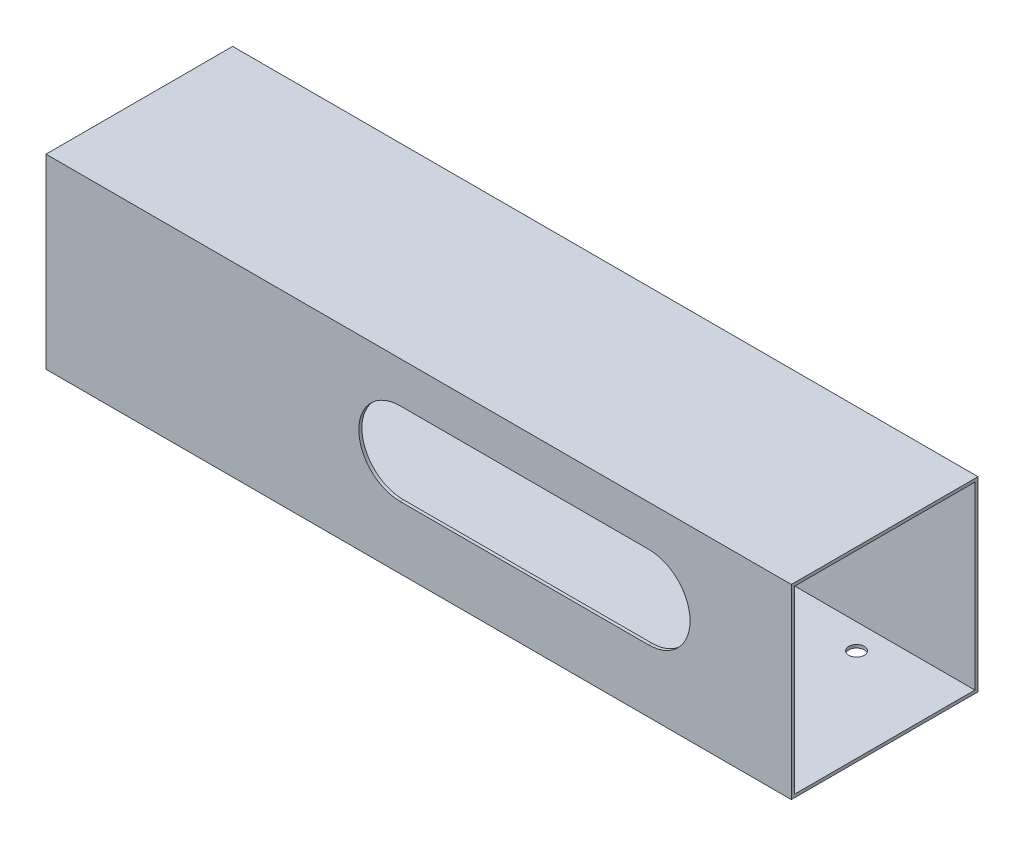
SolidWorks part; units mm, degrees
material "Liga 1350"
ref_plane "Plano frontal" through (0, 0, 0) normal (0, 0, 1) x (1, 0, 0)
ref_plane "Plano superior" through (0, 0, 0) normal (0, 1, 0) x (1, 0, 0)
ref_plane "Plano direito" through (0, 0, 0) normal (1, 0, 0) x (0, 0, -1)
sketch "Esboço2" plane through (0, 0, 0) normal (1, 0, 0) x (0, 0, -1)
  line L0 (-29, 40.0924) -> (-29, -17.9076)
  line L1 (-30, 41.0924) -> (30.1, 41.0924)
  line L2 (-30, 41.0924) -> (-30, -18.9076)
  line L3 (-30, -18.9076) -> (30.1, -18.9076)
  line L4 (30.1, 41.0924) -> (30.1, -18.9076)
  line L5 (-29, -17.9076) -> (29.1, -17.9076)
  line L6 (29.1, 40.0924) -> (29.1, -17.9076)
  line L7 (-29, 40.0924) -> (29.1, 40.0924)
  dimension "D1" = 30
  dimension "D2" = 60
  dimension "D3" = 1
  dimension "D4" = 30.1
  dimension "D5" = 1
  dimension "D6" = 1
  dimension "D7" = 1
extrude "Ressalto-extrusão3" add sketch "Esboço2" along normal blind 240
sketch "Esboço4" plane through (0, 0, 0) normal (0, 1, 0) x (1, 0, 0)
  line L0 (0, 0) -> (240, 0) construction
  line L1 (0, 30.1) -> (0, -30) construction
  line L2 (27, 0) -> (27, 41.6402) construction
  line L3 (240, 30.1) -> (240, -30) construction
  circle A0 centre (12, 15) radius 2
  circle A1 centre (12, -15) radius 2
  circle A2 centre (42, -15) radius 2
  circle A3 centre (42, 15) radius 2
  circle A4 centre (210, -21) radius 2.5
  circle A5 centre (210, 21) radius 2.5
  circle A6 centre (99, -21) radius 2.5
  circle A7 centre (99, 21) radius 2.5
  dimension "D1" = 4
  dimension "D11" = 5
  dimension "D2" = 15
  dimension "D3" = 12
  dimension "D4" = 15
  dimension "D5" = 42
  dimension "D6" = 21
  dimension "D7" = 30
  dimension "D8" = 57
  dimension "D9" = 42
  dimension "D10" = 21
extrude "Corte-extrusão1" cut sketch "Esboço4" against normal through all
sketch "Esboço5" plane through (0, 0, 30) normal (0, 0, 1) x (1, 0, 0)
  line L0 (194.0513, 14.5924) -> (114.0513, 14.5924) construction
  line L1 (194.0513, 1.2599) -> (114.0513, 1.2599)
  line L2 (194.0513, 27.9249) -> (114.0513, 27.9249)
  line L5 (240, 41.0924) -> (240, -18.9076) construction
  arc A0 (194.0513, 1.2599) -> (194.0513, 27.9249) centre (194.0513, 14.5924) ccw
  arc A1 (114.0513, 27.9249) -> (114.0513, 1.2599) centre (114.0513, 14.5924) ccw
  point P2 (154.0513, 14.5924)
  dimension "D1" = 80
  dimension "D2" = 45.9487
extrude "Corte-extrusão2" cut sketch "Esboço5" against normal blind 10
